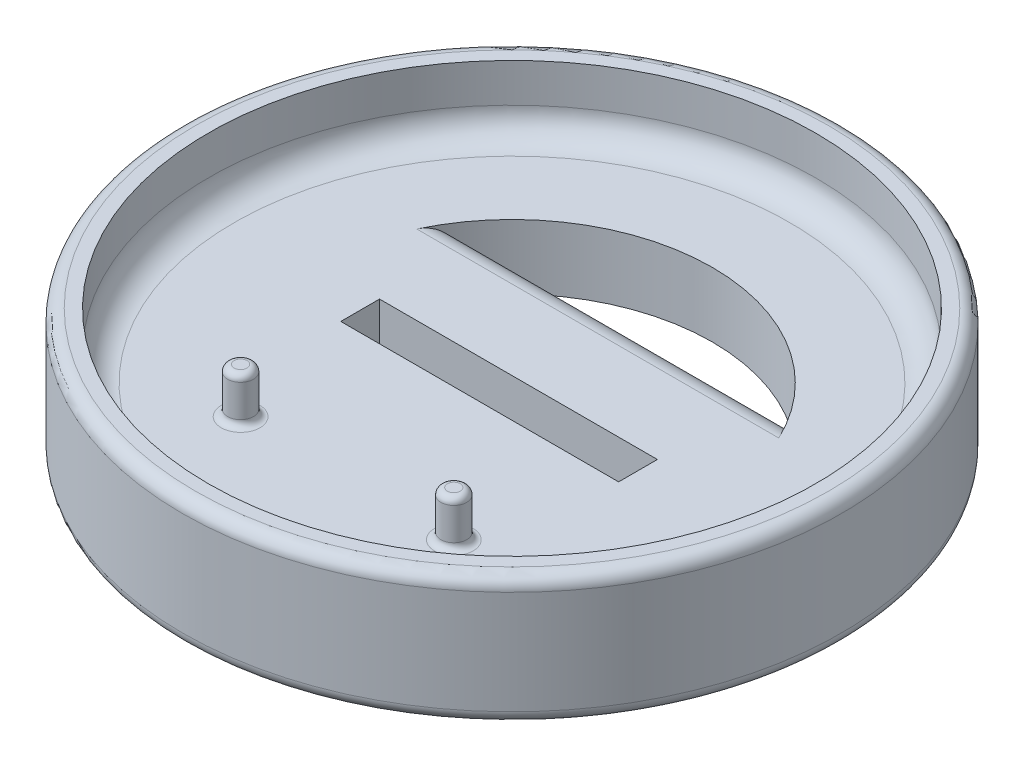
SolidWorks part; units mm, degrees
ref_plane "Front Plane" through (0, 0, 0) normal (0, 0, 1) x (1, 0, 0)
ref_plane "Top Plane" through (0, 0, 0) normal (0, 1, 0) x (1, 0, 0)
ref_plane "Right Plane" through (0, 0, 0) normal (1, 0, 0) x (0, 0, -1)
sketch "Sketch1" plane through (0, 0, 0) normal (0, 1, 0) x (1, 0, 0)
  line L0 (-12.8718, 8.6352) -> (12.8718, 8.6352)
  circle A0 centre (0, 0) radius 25.5
  circle A1 centre (0, 0) radius 15.5
  point P7 (0, 8.6352)
  dimension "D1" = 51
  dimension "D2" = 31
  dimension "D3" = 8.6352
extrude "Boss-Extrude1" add sketch "Sketch1" along normal blind 5 contours L0 A1 | A0 A1
sketch "Sketch2" plane through (0, 5, 0) normal (0, 1, 0) x (1, 0, 0)
  circle A0 centre (0, 0) radius 23.5
  circle A1 centre (0, 0) radius 25.5
  dimension "D1" = 47
  dimension "D2" = 51
extrude "Boss-Extrude2" add sketch "Sketch2" along normal blind 5
fillet "Fillet1" radius 2 3 edges at (0, 5, 23.5) (0, 0, -8.6352) (0, 5, -8.6352)
sketch "Sketch3" plane through (0, 5, 0) normal (0, 1, 0) x (1, 0, 0)
  line L1 (10.75, -14.5) -> (-10.75, -14.5)
  line L2 (10.75, -14.5) -> (10.75, 0.5)
  line L3 (10.75, 0.5) -> (-10.75, 0.5)
  line L4 (-10.75, -14.5) -> (-10.75, 0.5)
  line L5 (10.75, -14.5) -> (-10.75, 0.5) construction
  line L6 (10.75, 0.5) -> (-10.75, -14.5) construction
  line L7 (10.75, 0.5) -> (-10.75, 0.5)
  line L8 (10.75, 0.5) -> (10.75, -2.5)
  line L9 (10.75, -2.5) -> (-10.75, -2.5)
  line L10 (-10.75, 0.5) -> (-10.75, -2.5)
  point P0 (0, -7)
  dimension "D1" = 21.5
  dimension "D2" = 15
  dimension "D3" = 7
  dimension "D4" = 3
extrude "Cut-Extrude1" cut sketch "Sketch3" against normal blind 5 contours L9 L2 L3 L4
sketch "Sketch5" plane through (0, 5, 0) normal (0, 1, 0) x (1, 0, 0)
  line L1 (10.75, -2.5) -> (-10.75, -2.5)
  line L2 (10.75, -2.5) -> (10.75, -14.5)
  line L3 (10.75, -14.5) -> (-10.75, -14.5)
  line L4 (-10.75, -2.5) -> (-10.75, -14.5)
  line L5 (10.75, -14.5) -> (8.25, -14.5)
  line L6 (10.75, -14.5) -> (10.75, -12.75)
  line L7 (10.75, -12.75) -> (8.25, -12.75)
  line L8 (8.25, -14.5) -> (8.25, -12.75)
  line L9 (-10.75, -14.5) -> (-8.25, -14.5)
  line L10 (-10.75, -14.5) -> (-10.75, -12.75)
  line L11 (-10.75, -12.75) -> (-8.25, -12.75)
  line L12 (-8.25, -14.5) -> (-8.25, -12.75)
  circle A0 centre (8.25, -12.75) radius 1
  circle A1 centre (-8.25, -12.75) radius 1
  dimension "D7" = 2
  dimension "D8" = 2
  dimension "D1" = 21.5
  dimension "D2" = 12
  dimension "D3" = 2.5
  dimension "D4" = 1.75
  dimension "D5" = 1.75
  dimension "D6" = 2.5
extrude "Boss-Extrude3" add sketch "Sketch5" along normal blind 3.5 contours L8 A0 L7 | L7 A0 L8 | L11 A1 L12 | L12 A1 L11
fillet "Fillet2" radius 0.5 4 edges at (-8.25, 8.5, 13.75) (-8.25, 5, 13.75) (8.25, 8.5, 13.75) (8.25, 5, 13.75)
fillet "Fillet3" radius 1 2 edges at (0, 10, 25.5) (0, 0, 25.5)
